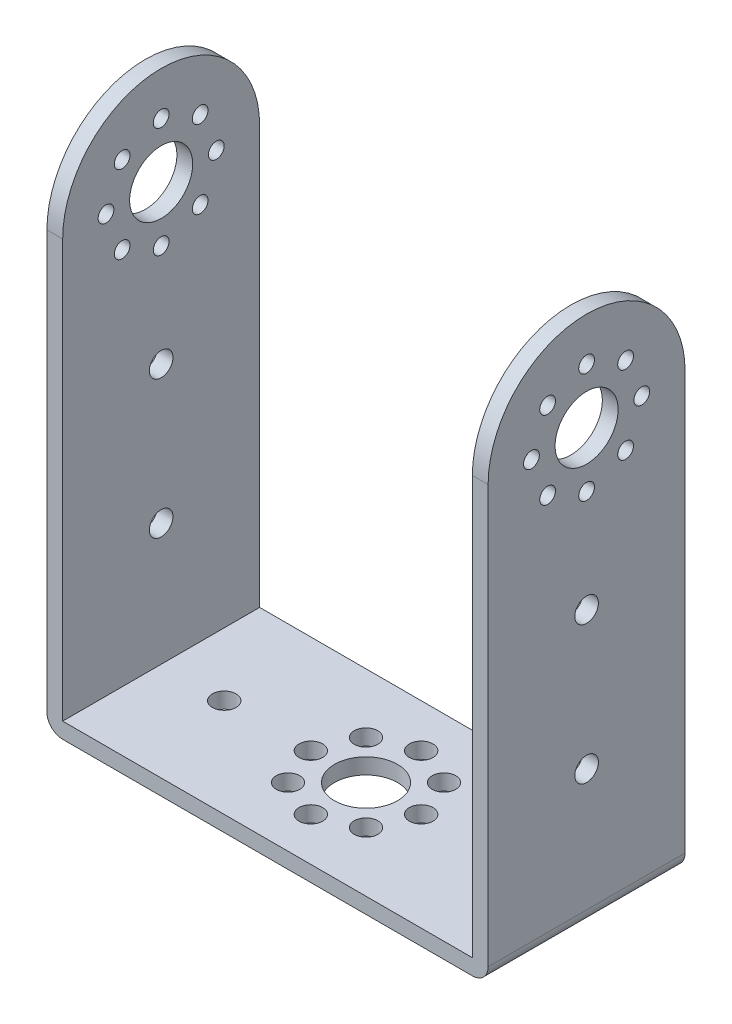
SolidWorks part; units mm, degrees
material "1.5714 (16NiCr4)"
ref_plane "前视基准面" through (0, 0, 0) normal (0, 0, 1) x (1, 0, 0)
ref_plane "上视基准面" through (0, 0, 0) normal (0, 1, 0) x (1, 0, 0)
ref_plane "右视基准面" through (0, 0, 0) normal (1, 0, 0) x (0, 0, -1)
sketch "草图1" plane through (0, 0, 0) normal (0, 1, 0) x (1, 0, 0)
  line L0 (-13.84, 11.7067) -> (-13.84, -13.2933)
  line L1 (-13.84, -13.2933) -> (42.16, -13.2933)
  line L2 (42.16, -13.2933) -> (42.16, 11.7067)
  line L3 (42.16, 11.7067) -> (-13.84, 11.7067)
  dimension "D1" = 56
  dimension "D2" = 25
extrude "凸台-拉伸1" add sketch "草图1" along normal blind 2
ref_plane "基准面4" through (42.16, 0, 0) normal (1, 0, 0) x (0, 0, -1)
sketch "草图2" plane through (42.16, 0, 0) normal (1, 0, 0) x (0, 0, -1)
  line L0 (-13.2933, 2) -> (-13.2933, 55)
  line L1 (11.7067, 2) -> (11.7067, 55)
  line L2 (-13.2933, 2) -> (11.7067, 2)
  arc A0 (-13.2933, 55) -> (11.7067, 55) centre (-0.7933, 55) cw
extrude "凸台-拉伸2" add sketch "草图2" against normal blind 2
ref_plane "基准面5" through (14.16, 0, 0) normal (-1, 0, 0) x (0, 0, 1)
mirror "镜向1" about plane through (14.16, 0, 0) normal (-1, 0, 0) of "凸台-拉伸2"
sketch "草图3" plane through (42.16, 0, 0) normal (1, 0, 0) x (0, 0, -1)
  line L0 (-13.2933, 55) -> (11.7067, 55) construction
  circle A0 centre (-0.7933, 55) radius 4
  circle A1 centre (-0.7933, 55) radius 7 construction
  circle A2 centre (-0.7933, 62) radius 1
  circle A3 centre (4.1564, 59.9497) radius 1
  circle A4 centre (6.2067, 55) radius 1
  circle A5 centre (4.1564, 50.0503) radius 1
  circle A6 centre (-0.7933, 48) radius 1
  circle A7 centre (-5.7431, 50.0503) radius 1
  circle A8 centre (-7.7933, 55) radius 1
  circle A9 centre (-5.7431, 59.9497) radius 1
  point P26 (-0.7933, 55)
  dimension "D1" = 8
  dimension "D2" = 14
  dimension "D3" = 8
extrude "切除-拉伸1" cut sketch "草图3" against normal blind 105
sketch "草图4" plane through (42.16, 0, 0) normal (1, 0, 0) x (0, 0, -1)
  line L0 (-0.7933, 55) -> (-0.7933, 0) construction
  line L1 (-13.2933, 0) -> (11.7067, 0) construction
  line L2 (-0.7933, 0) -> (-0.7933, 17.5) construction
  circle A0 centre (-0.7933, 17.5) radius 1.5
  circle A1 centre (-0.7933, 35) radius 1.5
  dimension "D1" = 2
extrude "切除-拉伸2" cut sketch "草图4" against normal blind 105
sketch "草图5" plane through (0, 2, 0) normal (0, 1, 0) x (1, 0, 0)
  line L0 (-13.84, -13.2933) -> (-3.84, -13.2933)
  line L1 (-11.84, -13.2933) -> (40.16, -13.2933) construction
  line L2 (-3.84, -13.2933) -> (-3.84, 11.7067)
  line L3 (40.16, 11.7067) -> (-11.84, 11.7067) construction
  line L4 (14.16, 13.75) -> (14.16, -13.75) construction
  circle A0 centre (-3.84, -0.7933) radius 1.5
  circle A1 centre (32.16, -0.7933) radius 1.5
extrude "切除-拉伸3" cut sketch "草图5" against normal blind 105 contours A1 | L2 A0 | L2 A0
sketch "草图6" plane through (0, 2, 0) normal (0, 1, 0) x (1, 0, 0)
  line L0 (32.474, -13.2933) -> (32.474, 11.7067)
  line L1 (-11.84, -13.2933) -> (40.16, -13.2933) construction
  line L2 (40.16, 11.7067) -> (-11.84, 11.7067) construction
  line L5 (14.16, 13.75) -> (14.16, -13.75) construction
  circle A0 centre (14.16, -0.7933) radius 4
  circle A1 centre (14.16, -0.7933) radius 7 construction
  circle A2 centre (14.16, -7.7933) radius 1.5
  circle A3 centre (9.2103, -5.7431) radius 1.5
  circle A4 centre (7.16, -0.7933) radius 1.5
  circle A5 centre (9.2103, 4.1564) radius 1.5
  circle A6 centre (14.16, 6.2067) radius 1.5
  circle A7 centre (19.1097, 4.1564) radius 1.5
  circle A8 centre (21.16, -0.7933) radius 1.5
  circle A9 centre (19.1097, -5.7431) radius 1.5
  point P34 (14.16, -0.7933)
  dimension "D1" = 8
extrude "切除-拉伸5" cut sketch "草图6" against normal blind 105 contours A2 | A3 | A4 | A5 | A6 | A7 | A8 | A9 | A0
sketch "草图7" plane through (0, 0, 13.2933) normal (0, 0, 1) x (1, 0, 0)
  line L0 (-13.84, 2) -> (-13.84, 23.8127)
  line L1 (-13.84, 55) -> (-13.84, 0) construction
  line L2 (-11.84, 0) -> (14.16, 0)
  line L3 (-13.84, 0) -> (42.16, 0) construction
  line L4 (-13.84, 2) -> (-13.84, 0)
  line L5 (-13.84, 0) -> (-11.84, 0)
  line L6 (14.16, 13.75) -> (14.16, -13.75) construction
  line L7 (42.16, 2) -> (42.16, 0)
  line L8 (42.16, 0) -> (40.16, 0)
  arc A0 (-13.84, 2) -> (-11.84, 0) centre (-11.84, 2) ccw
  arc A1 (42.16, 2) -> (40.16, 0) centre (40.16, 2) cw
  point P10 (-13.84, 0)
  line M2 (-13.84, 0) -> (42.16, 0)
  line M3 (42.16, 0) -> (42.16, 55)
  line M9 (-13.84, 55) -> (-13.84, 0)
  dimension "D1" = 2
extrude "切除-拉伸6" cut sketch "草图7" against normal through all contours A0 M9 M2 | A1 M3 M2
